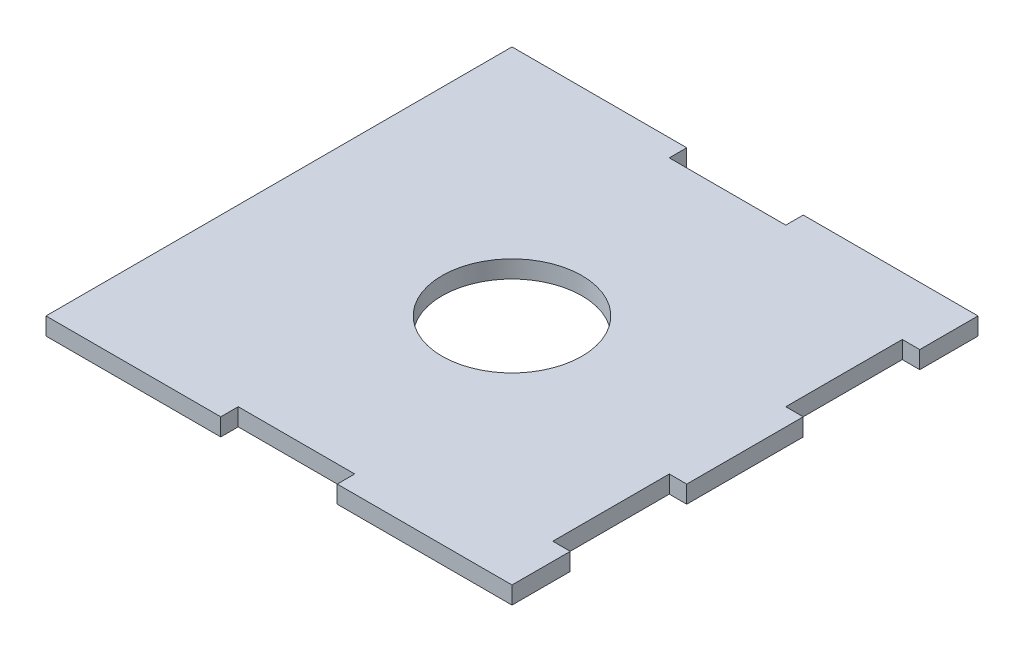
SolidWorks part; units mm, degrees
ref_plane "Alzado" through (0, 0, 0) normal (0, 0, 1) x (1, 0, 0)
ref_plane "Planta" through (0, 0, 0) normal (0, 1, 0) x (1, 0, 0)
ref_plane "Vista lateral" through (0, 0, 0) normal (1, 0, 0) x (0, 0, -1)
sketch "Croquis1" plane through (0, 0, 0) normal (0, 1, 0) x (1, 0, 0)
  line L1 (-40, 40) -> (-10, 40)
  line L2 (-40, 40) -> (-40, -40)
  line L3 (-40, -40) -> (-10, -40)
  line L4 (37, 30) -> (40, 30)
  line L5 (-40, 40) -> (40, -40) construction
  line L6 (-40, -40) -> (40, 40) construction
  line L49 (10, -40) -> (37, -40)
  line L50 (40, -30) -> (40, -40)
  line L51 (37, -10) -> (37, -30)
  line L52 (40, 10) -> (37, 10)
  line L53 (37, 40) -> (40, 40)
  line L54 (40, 10) -> (40, -10)
  line L55 (37, -10) -> (40, -10)
  line L56 (40, -30) -> (37, -30)
  line L58 (0, 37) -> (-10, 37)
  line L59 (0, 37) -> (10, 37)
  line L60 (10, 37) -> (10, 40)
  line L61 (-10, 37) -> (-10, 40)
  line L62 (10, 40) -> (37, 40)
  line L63 (-10, -37) -> (-10, -40)
  line L64 (10, -37) -> (10, -40)
  line L65 (0, -37) -> (10, -37)
  line L66 (0, -37) -> (-10, -37)
  line L68 (40, 40) -> (40, 30)
  line L69 (40, -40) -> (37, -40)
  line L70 (37, 30) -> (37, 10)
  circle A0 centre (0, 0) radius 12
  dimension "D3" = 24
  dimension "D1" = 80
  dimension "D2" = 80
  dimension "D16" = 10
  dimension "D17" = 10
extrude "Saliente-Extruir1" add sketch "Croquis1" along normal blind 3
